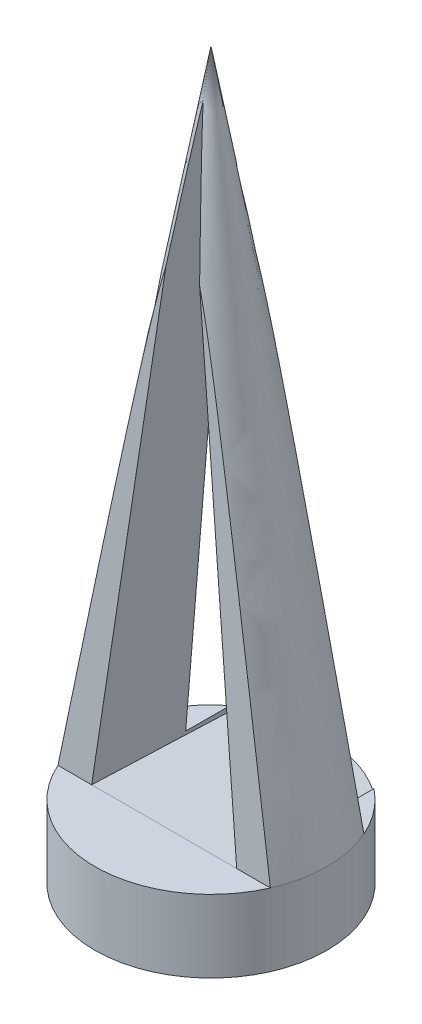
SolidWorks part; units mm, degrees
ref_plane "Front Plane" through (0, 0, 0) normal (0, 0, 1) x (1, 0, 0)
ref_plane "Top Plane" through (0, 0, 0) normal (0, 1, 0) x (1, 0, 0)
ref_plane "Right Plane" through (0, 0, 0) normal (1, 0, 0) x (0, 0, -1)
sketch "Sketch1" plane through (0, 0, 0) normal (0, 0, 1) x (1, 0, 0)
  line L0 (0, 0) -> (0, 100) construction
  line L1 (-15, 0) -> (15, 0) construction
  line L2 (0, 100) -> (-16, 10)
  line L9 (-16, 0) -> (-16, 10)
  line L13 (-16, 0) -> (0, 0)
  line L14 (0, 0) -> (0, 100)
  point P6 (0, 0)
revolve "Revolve1" add sketch "Sketch1" angle 360 about L14
sketch "Sketch3" plane through (0, 0, 0) normal (1, 0, 0) x (0, 0, -1)
  line L0 (-29.452, 10) -> (-6.452, 10)
  line L2 (-29.452, 10) -> (-29.452, 110.8196)
  line L3 (-29.452, 110.8196) -> (-2.452, 110.8196)
  line L4 (16, 10) -> (-16, 10) construction
  line L5 (-6.452, 10) -> (-2.452, 110.8196)
  line L6 (0, -50) -> (0, 50) construction
  line L7 (29.452, 10) -> (6.452, 10)
  line L8 (29.452, 10) -> (29.452, 110.8196)
  line L9 (29.452, 110.8196) -> (2.452, 110.8196)
  line L10 (6.452, 10) -> (2.452, 110.8196)
  dimension "D1" = 29.452
  dimension "D2" = 29.452
extrude "Cut-Extrude1" cut sketch "Sketch3" against normal through all both and the other way through all
sketch "Sketch4" plane through (0, 0.2713, 6.838) normal (0, 0.0396, 0.9992) x (1, 0, 0)
  line L1 (-14.6414, 9.7364) -> (14.6414, 9.7364) construction
  line L2 (-10, 9.7364) -> (10, 9.7364)
  line L3 (10, 9.7364) -> (0, 93.8395)
  line L4 (0, 93.8395) -> (-10, 9.7364)
  point P0 (0, 93.8395)
  point P7 (0, 9.7364)
extrude "Cut-Extrude2" cut sketch "Sketch4" against normal through all both and the other way through all
